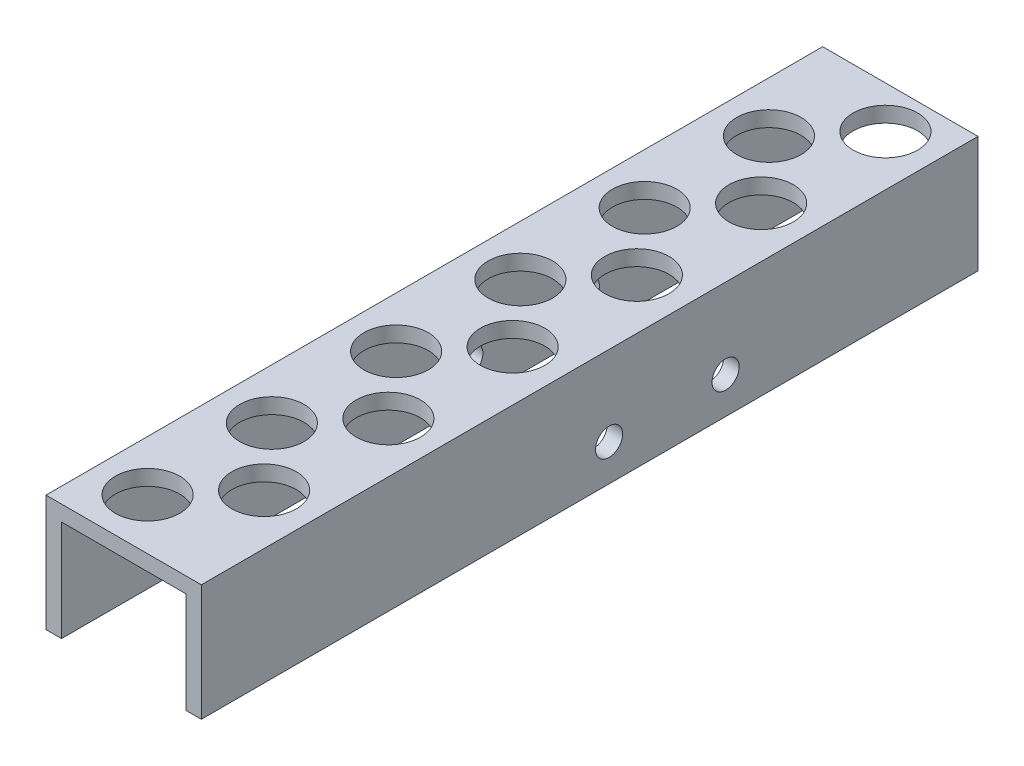
SolidWorks part; units mm, degrees
ref_plane "Alzado" through (0, 0, 0) normal (0, 0, 1) x (1, 0, 0)
ref_plane "Planta" through (0, 0, 0) normal (0, 1, 0) x (1, 0, 0)
ref_plane "Vista lateral" through (0, 0, 0) normal (1, 0, 0) x (0, 0, -1)
sketch "Croquis1" plane through (0, 0, 0) normal (0, 0, 1) x (1, 0, 0)
  line L1 (-10, -7.5) -> (10, -7.5)
  line L2 (-10, -7.5) -> (-10, 7.5)
  line L3 (-10, 7.5) -> (10, 7.5)
  line L4 (10, -7.5) -> (10, 7.5)
  line L5 (-10, -7.5) -> (10, 7.5) construction
  line L6 (-10, 7.5) -> (10, -7.5) construction
  point P0 (0, 0)
  dimension "D1" = 20
  dimension "D2" = 15
extrude "Saliente-Extruir1" add sketch "Croquis1" along normal blind 100
sketch "Croquis2" plane through (0, 0, 0) normal (0, 0, -1) x (-1, 0, 0)
  line L0 (10, -7.5) -> (-10, -7.5) construction
  line L1 (-8, -7.5) -> (8, -7.5)
  line L2 (-8, -7.5) -> (-8, 5.5)
  line L3 (-8, 5.5) -> (8, 5.5)
  line L4 (8, -7.5) -> (8, 5.5)
  line L5 (-10, -7.5) -> (-10, 7.5) construction
  point P0 (0, 0)
  dimension "D1" = 16
  dimension "D2" = 13
  dimension "D3" = 2
sketch "Croquis3" plane through (0, 7.5, 0) normal (0, 1, 0) x (1, 0, 0)
  line L0 (-10, -100) -> (-10, 0) construction
  line L1 (10, -100) -> (10, 0) construction
  circle A0 centre (3.5, -5.4191) radius 4.15
  circle A1 centre (-3.5, -13.4191) radius 4.15
  circle A2 centre (3.5, -21.4191) radius 4.15
  circle A3 centre (-3.5, -29.4191) radius 4.15
  circle A4 centre (3.5, -37.4191) radius 4.15
  circle A5 centre (-3.5, -45.4191) radius 4.15
  circle A6 centre (3.5, -53.4191) radius 4.15
  circle A7 centre (-3.5, -61.4191) radius 4.15
  circle A8 centre (3.5, -69.4191) radius 4.15
  circle A9 centre (-3.5, -77.4191) radius 4.15
  circle A10 centre (3.5, -85.4191) radius 4.15
  circle A11 centre (-3.5, -93.4191) radius 4.15
  dimension "D1" = 8.3
  dimension "D2" = 8.3
  dimension "D5" = 8
  dimension "D6" = 6
  dimension "D3" = 6.5
  dimension "D4" = 6.5
extrude "Cortar-Extruir2" cut sketch "Croquis2" against normal blind 100
extrude "Cortar-Extruir3" cut sketch "Croquis3" against normal blind 2
sketch "Croquis4" plane through (10, 0, 0) normal (1, 0, 0) x (0, 0, -1)
  line L0 (-100, -7.5) -> (0, -7.5) construction
  line L2 (0, -7.5) -> (0, 7.5) construction
  circle A0 centre (-32.5, -2.8) radius 1.75
  circle A1 centre (-47.5, -2.8) radius 1.75
  dimension "D1" = 3.5
  dimension "D4" = 3.5
  dimension "D6" = 15
  dimension "D2" = 4.7
  dimension "D3" = 32.5
  dimension "D5" = 4.7
extrude "Cortar-Extruir5" cut sketch "Croquis4" against normal through all and the other way through all
